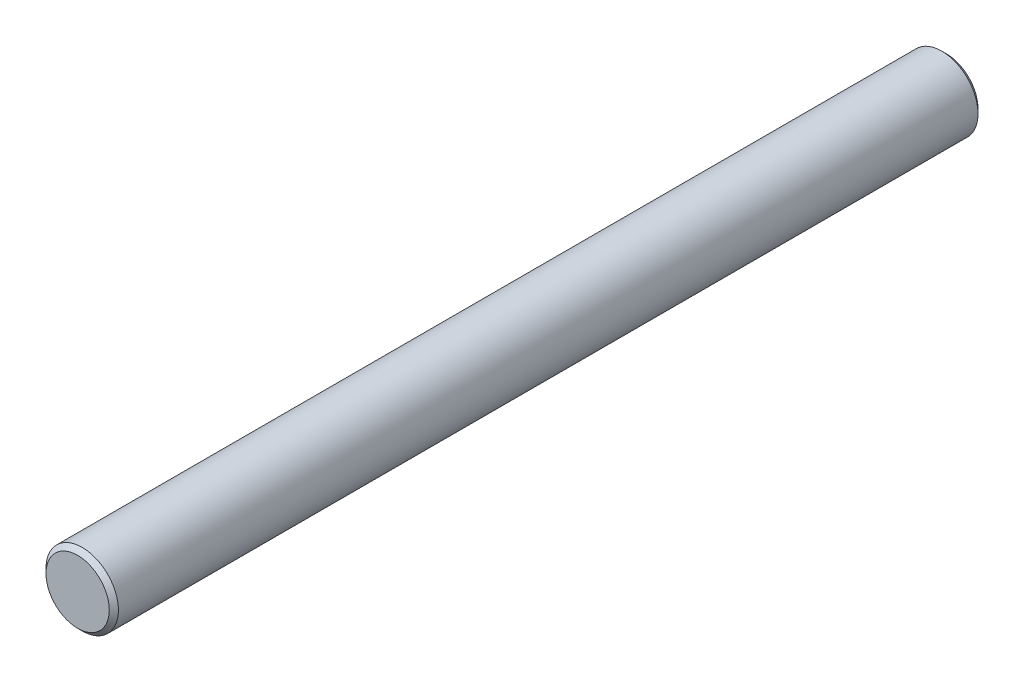
SolidWorks part; units mm, degrees
ref_plane "Front Plane" through (0, 0, 0) normal (0, 0, 1) x (1, 0, 0)
ref_plane "Top Plane" through (0, 0, 0) normal (0, 1, 0) x (1, 0, 0)
ref_plane "Right Plane" through (0, 0, 0) normal (1, 0, 0) x (0, 0, -1)
sketch "Sketch1" plane through (0, 0, 0) normal (0, 0, 1) x (1, 0, 0)
  circle A0 centre (0, 0) radius 3.175
  dimension "D1" = 6.35
extrude "Boss-Extrude1" add sketch "Sketch1" along normal blind 76.2
chamfer "Chamfer1" distance 0.4 angle 45 2 edges at (3.175, 0, 76.2) (3.175, 0, 0)
